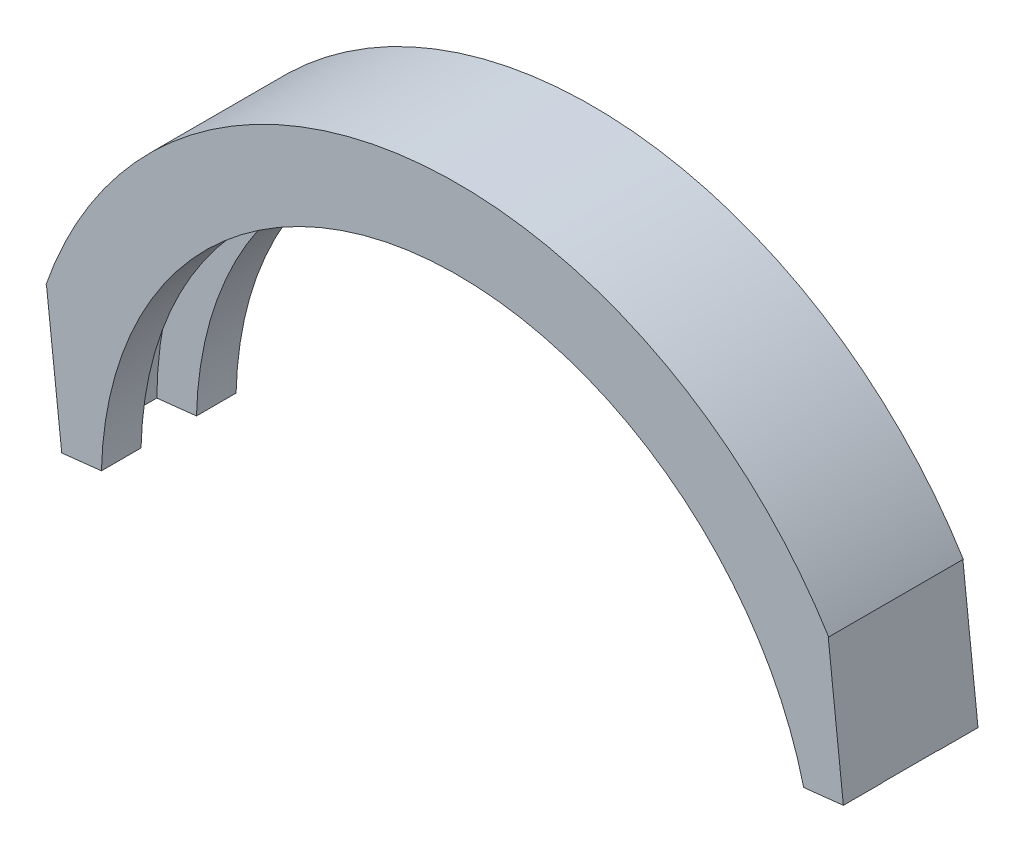
SolidWorks part; units mm, degrees
ref_plane "Front Plane" through (0, 0, 0) normal (0, 0, 1) x (1, 0, 0)
ref_plane "Top Plane" through (0, 0, 0) normal (0, 1, 0) x (1, 0, 0)
ref_plane "Right Plane" through (0, 0, 0) normal (1, 0, 0) x (0, 0, -1)
sketch "Sketch1" plane through (0, 0, 0) normal (0, 1, 0) x (1, 0, 0)
  line L1 (0, 0) -> (-50, 0)
  line L2 (0, 0) -> (0, 7)
  line L3 (0, 7) -> (-50, 7)
  line L4 (-50, 0) -> (-50, 7)
revolve "Revolve1" add sketch "Sketch1" angle 167.5 about L2
shell "Shell7" thickness 5
sketch "Sketch2" plane through (0, 0, 5) normal (0, 0, 1) x (1, 0, 0)
  line L0 (-55, 0) -> (53.6963, 11.9042)
extrude "Cut-Extrude1" cut sketch "Sketch2" against normal blind 10 and the other way through all flip side to cut contours L0
sketch "Sketch4" plane through (0, 0, -12) normal (0, 0, -1) x (-1, 0, 0)
  line L0 (-53.6963, 11.9042) -> (55, 0)
extrude "Cut-Extrude2" cut sketch "Sketch4" against normal blind 10 and the other way through all flip side to cut
sketch "Sketch5" plane through (0, 0, 5) normal (0, 0, 1) x (1, 0, 0)
  line L0 (53.6963, 11.9042) -> (-55, 0) construction
  arc A0 (-44.9866, 1.0966) -> (43.6829, 10.8075) centre (0, 0) cw
sketch "Sketch6" plane through (0, 0, -12) normal (0, 0, -1) x (-1, 0, 0)
  arc A0 (-43.6829, 10.8075) -> (44.9866, 1.0966) centre (0, 0) cw
  arc A1 (44.9866, 1.0966) -> (-43.6829, 10.8075) centre (0, 0) ccw construction
extrude "Cut-Extrude3" cut sketch "Sketch5" against normal blind 10 and the other way through all flip side to cut contours A0
extrude "Cut-Extrude4" cut sketch "Sketch6" against normal blind 10 and the other way through all flip side to cut contours A0
sketch "Sketch13" plane through (0, 0, 5) normal (0, 0, 1) x (1, 0, 0)
  line L3 (53.6963, 11.9042) -> (43.6829, 10.8075) construction
  line L7 (48.6896, 11.3559) -> (46.7755, 28.8337)
  line L8 (-50.0202, 0.5454) -> (-51.9279, 17.9644)
sketch "Sketch14" plane through (0, 0, 5) normal (0, 0, 1) x (1, 0, 0)
  line L0 (-49.997, 0.5479) -> (-51.9279, 17.9644)
extrude "Cut-Extrude-Thin2" cut sketch "Sketch13" against normal blind 20 and the other way through all thin contours L7
extrude "Cut-Extrude-Thin3" cut sketch "Sketch14" against normal blind 20 and the other way through all thin contours L0 thin type one direction reverse wall 10
